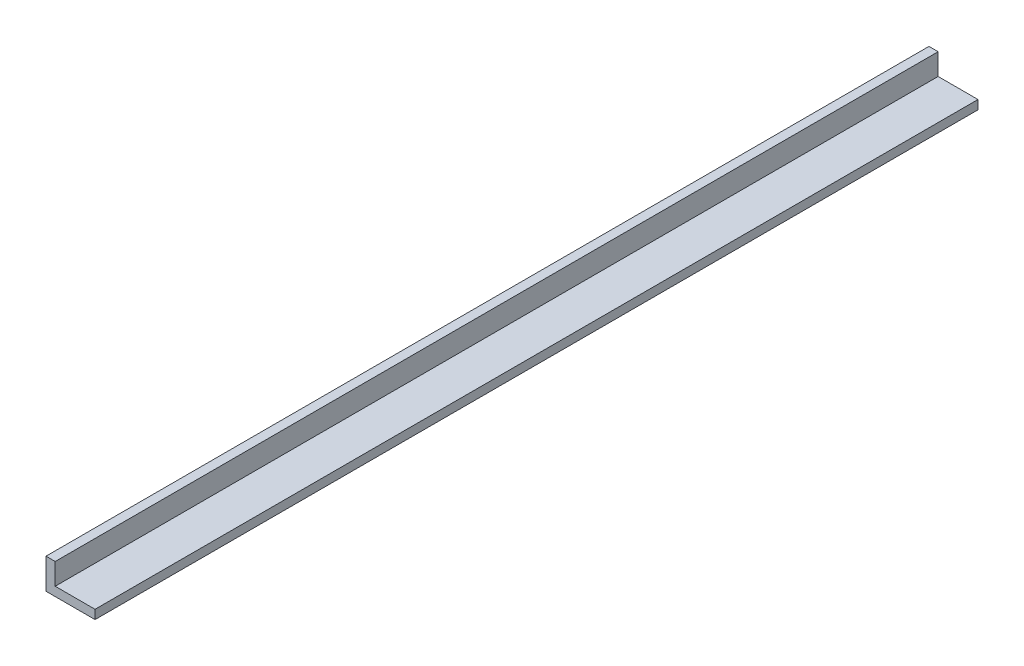
SolidWorks part; units mm, degrees
ref_plane "Front Plane" through (0, 0, 0) normal (0, 0, 1) x (1, 0, 0)
ref_plane "Top Plane" through (0, 0, 0) normal (0, 1, 0) x (1, 0, 0)
ref_plane "Right Plane" through (0, 0, 0) normal (1, 0, 0) x (0, 0, -1)
sketch "Sketch2" plane through (0, 0, 0) normal (0, 0, 1) x (1, 0, 0)
  line L1 (-102.9331, -18.8) -> (100.2669, -18.8)
  line L2 (-102.9331, -18.8) -> (-102.9331, 19.3)
  line L3 (-64.8459, 18.3131) -> (100.2669, 18.3131)
  line L4 (100.2669, -18.8) -> (100.2669, 18.3131)
  line L5 (-102.9331, -18.8) -> (100.2669, 18.3131) construction
  line L6 (-102.9331, 19.3) -> (100.2669, -18.8) construction
  line L8 (-102.9331, 19.3) -> (-102.9331, 107.2131)
  line L9 (-102.9331, 107.2131) -> (-64.8459, 107.2131)
  line L10 (-64.8459, 18.3131) -> (-64.8459, 107.2131)
  line L11 (-102.9331, 19.3) -> (-64.8459, 107.2131) construction
  line L12 (-102.9331, 107.2131) -> (-64.8459, 18.3131) construction
  point P0 (0, 0)
  point P9 (-83.9958, 63.0112)
  dimension "D1" = 38.1
  dimension "D2" = 203.2
  dimension "D3" = 88.9
  dimension "D4" = 38.1
extrude "Boss-Extrude1" add sketch "Sketch2" along normal blind 3657.6
